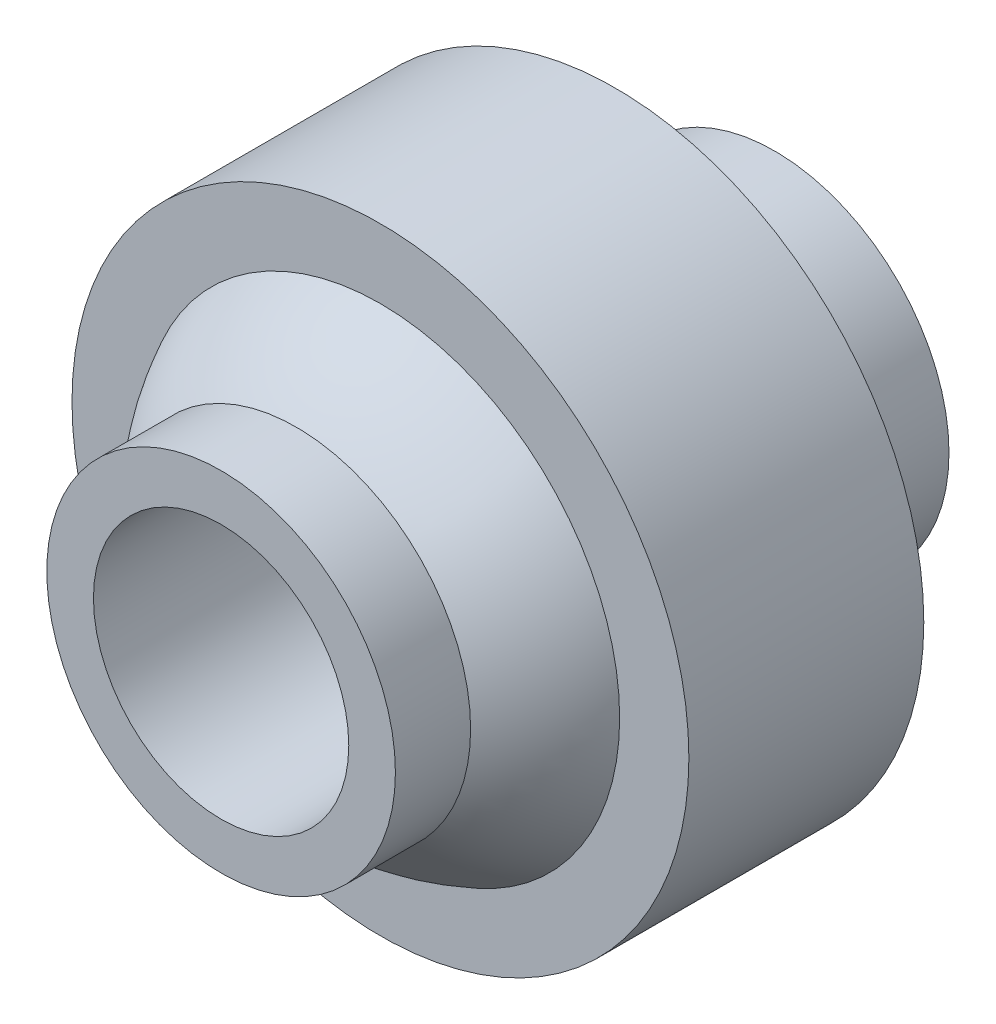
SolidWorks part; units mm, degrees
material "AISI 4130 Steel, normalized at 870C"
ref_plane "Front Plane" through (0, 0, 0) normal (0, 0, 1) x (1, 0, 0)
ref_plane "Top Plane" through (0, 0, 0) normal (0, 1, 0) x (1, 0, 0)
ref_plane "Right Plane" through (0, 0, 0) normal (1, 0, 0) x (0, 0, -1)
sketch "Sketch1" plane through (0, 0, 0) normal (1, 0, 0) x (0, 0, -1)
  line L0 (0, 0) -> (9.3814, 0) construction
  line L1 (0, 0) -> (0, 10.4361) construction
  line L2 (-10.3251, -4.7625) -> (10.3251, -4.7625)
  line L3 (10.3251, -4.7625) -> (10.3251, -6.5024)
  line L4 (10.3251, -6.5024) -> (7.52, -6.5024)
  line L5 (-10.3251, -4.7625) -> (-10.3251, -6.5024)
  line L6 (-10.3251, -6.5024) -> (-7.52, -6.5024)
  line L7 (-4.3815, -8.9238) -> (-4.3815, -11.5062)
  line L8 (-4.3815, -11.5062) -> (4.3815, -11.5062)
  line L9 (4.3815, -11.5062) -> (4.3815, -8.9238)
  line L10 (-7.52, -6.5024) -> (7.52, -6.5024) construction
  line L11 (-7.52, -6.5024) -> (0, 0) construction
  line L12 (0, 0) -> (-4.3815, -8.9238) construction
  arc A0 (-7.52, -6.5024) -> (-4.3815, -8.9238) centre (0, 0) ccw
  arc A1 (7.52, -6.5024) -> (4.3815, -8.9238) centre (0, 0) cw
  point P15 (0, -4.7625)
  point P18 (0, -11.5062)
  dimension "D3" = 8.763
  dimension "D1" = 20.6502
  dimension "D2" = 13.0048
  dimension "D4" = 23
  dimension "D5" = 9.525
  dimension "D6" = 23.0124
revolve "Revolve1" add sketch "Sketch1" angle 360 about L0
